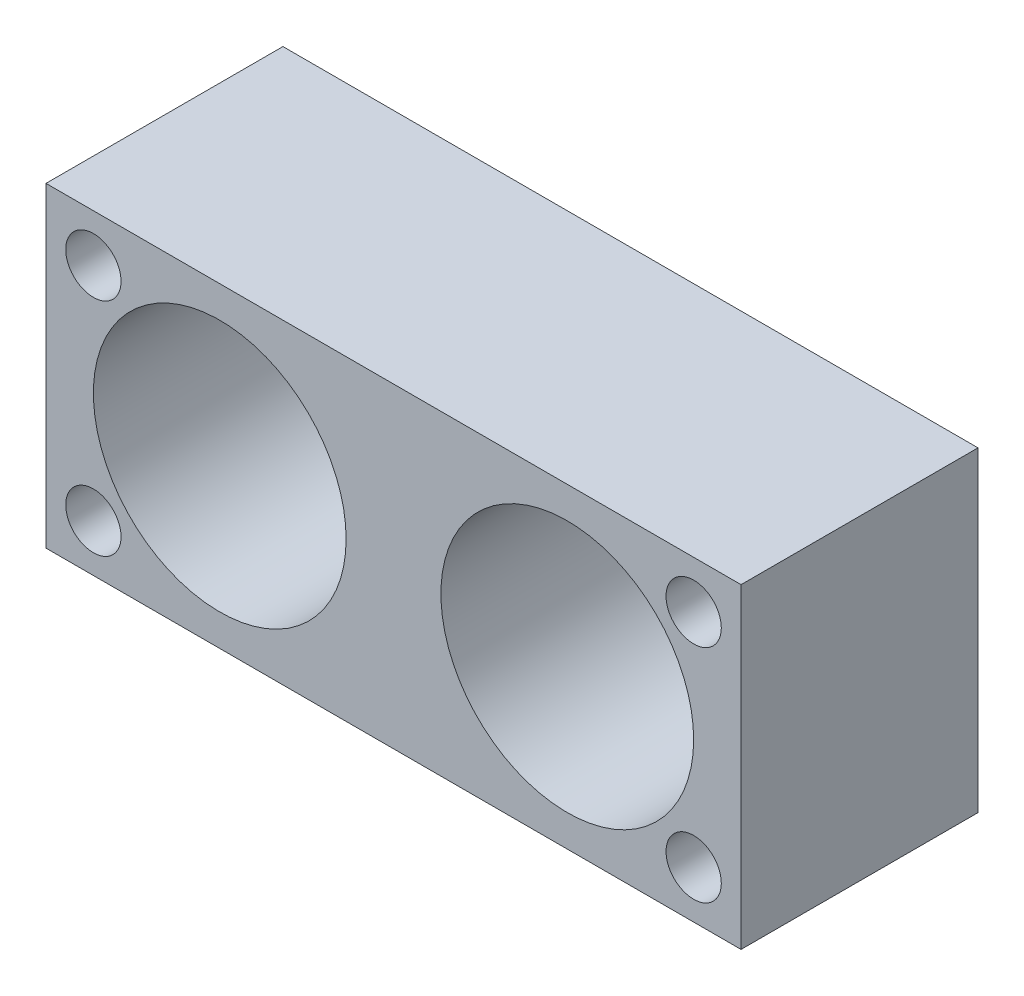
SolidWorks part; units mm, degrees
ref_plane "Alzado" through (0, 0, 0) normal (0, 0, 1) x (1, 0, 0)
ref_plane "Planta" through (0, 0, 0) normal (0, 1, 0) x (1, 0, 0)
ref_plane "Vista lateral" through (0, 0, 0) normal (1, 0, 0) x (0, 0, -1)
sketch "Croquis1" plane through (0, 0, 0) normal (0, 0, 1) x (1, 0, 0)
  line L0 (0, 15.6584) -> (0, -24.0356) construction
  line L1 (-22, 10) -> (22, 10)
  line L2 (-22, 10) -> (-22, -10)
  line L3 (-22, -10) -> (22, -10)
  line L4 (22, 10) -> (22, -10)
  line L5 (-37.1103, 0) -> (35.8577, 0) construction
  circle A0 centre (-11, 0) radius 8
  circle A1 centre (11, 0) radius 8
  dimension "D3" = 22
  dimension "D4" = 16
  dimension "D1" = 44
  dimension "D2" = 20
extrude "Saliente-Extruir1" add sketch "Croquis1" along normal blind 15
sketch "Croquis2" plane through (0, 0, 15) normal (0, 0, 1) x (1, 0, 0)
  line L0 (22, 10) -> (-22, 10) construction
  line L1 (-22, 10) -> (-22, -10) construction
  line L2 (22, -10) -> (22, 10) construction
  line L3 (-22, -10) -> (22, -10) construction
  line L4 (0, 15.8636) -> (0, -23.2706) construction
  line L5 (-26.8916, 0) -> (44.0827, 0) construction
  circle A0 centre (-19, 7) radius 1.75
  circle A1 centre (19, -7) radius 1.75
  circle A2 centre (19, 7) radius 1.75
  circle A3 centre (-19, -7) radius 1.75
  point P23 (-18.7835, 5.2634)
  dimension "D1" = 3.5
  dimension "D2" = 3.5
  dimension "D7" = 38
  dimension "D3" = 3
  dimension "D4" = 3
  dimension "D5" = 3
  dimension "D6" = 3
  dimension "D8" = 14
extrude "Cortar-Extruir1" cut sketch "Croquis2" against normal blind 22
